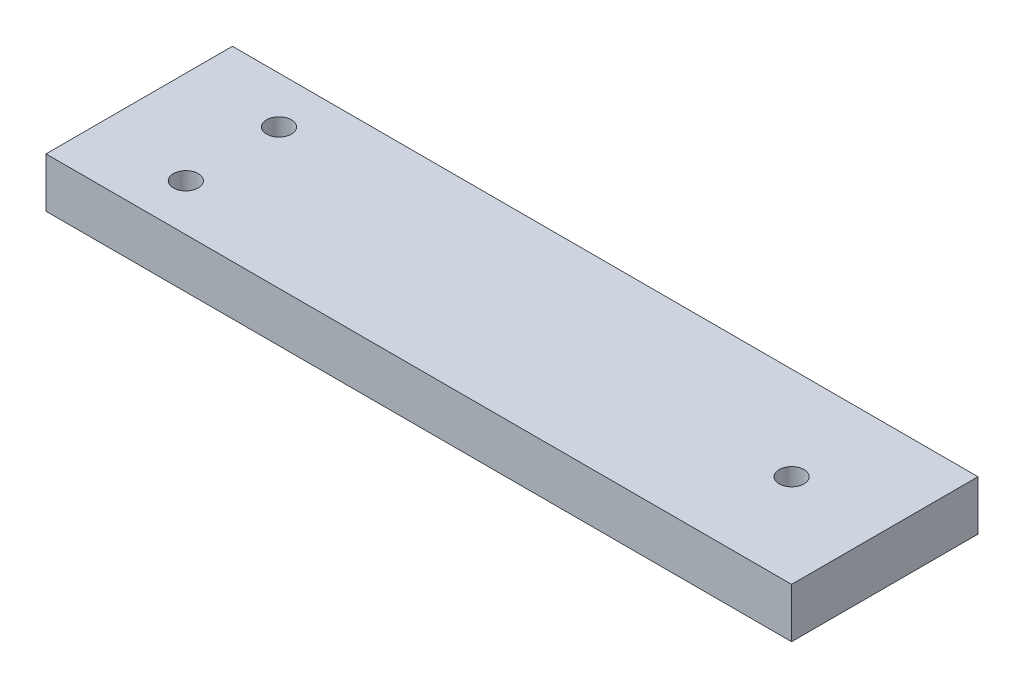
SolidWorks part; units mm, degrees
ref_plane "Front Plane" through (0, 0, 0) normal (0, 0, 1) x (1, 0, 0)
ref_plane "Top Plane" through (0, 0, 0) normal (0, 1, 0) x (1, 0, 0)
ref_plane "Right Plane" through (0, 0, 0) normal (1, 0, 0) x (0, 0, -1)
sketch "Sketch1" plane through (0, 0, 0) normal (0, 1, 0) x (1, 0, 0)
  line L0 (-45, 7.5) -> (-45, -7.5) construction
  line L1 (-60, 15) -> (60, 15)
  line L2 (-60, 15) -> (-60, -15)
  line L3 (-60, -15) -> (60, -15)
  line L4 (60, 15) -> (60, -15)
  line L5 (-60, 15) -> (60, -15) construction
  line L6 (-60, -15) -> (60, 15) construction
  circle A0 centre (45, 0) radius 2
  circle A1 centre (-45, -7.5) radius 2
  circle A2 centre (-45, 7.5) radius 2
  point P0 (0, 0)
  dimension "D3" = 4
  dimension "D4" = 4
  dimension "D5" = 15
  dimension "D6" = 15
  dimension "D7" = 7.5
  dimension "D8" = 4
  dimension "D9" = 15
  dimension "D10" = 7.5
  dimension "D1" = 30
  dimension "D2" = 120
extrude "Boss-Extrude1" add sketch "Sketch1" along normal blind 8
